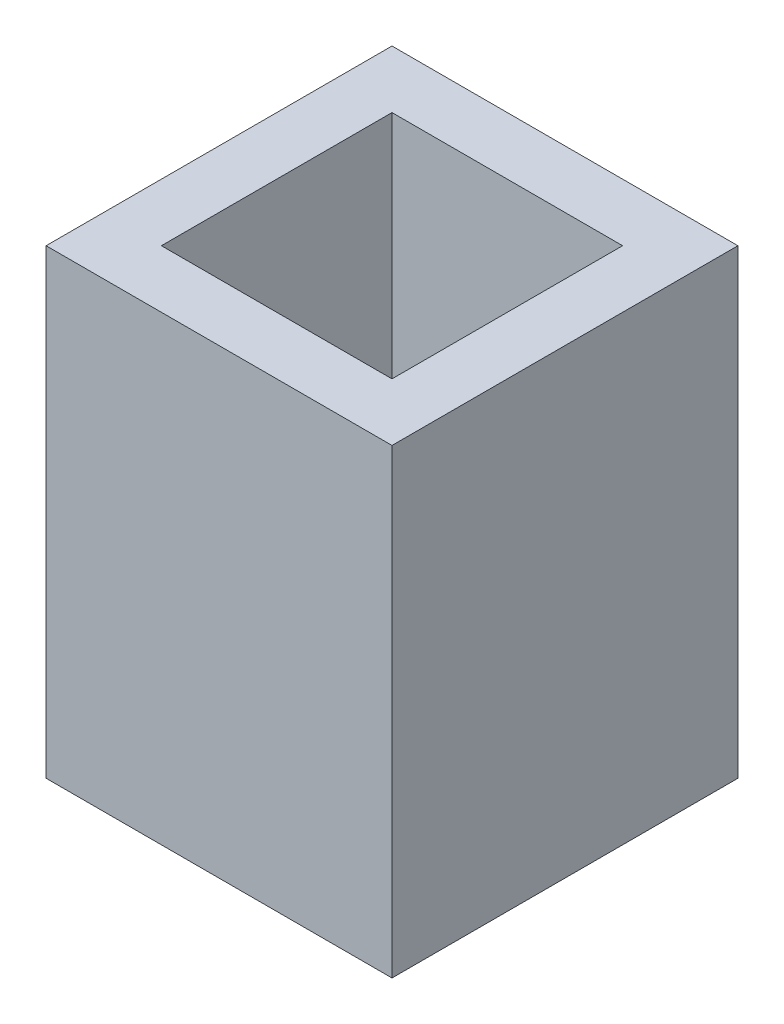
SolidWorks part; units mm, degrees
ref_plane "Front Plane" through (0, 0, 0) normal (0, 0, 1) x (1, 0, 0)
ref_plane "Top Plane" through (0, 0, 0) normal (0, 1, 0) x (1, 0, 0)
ref_plane "Right Plane" through (0, 0, 0) normal (1, 0, 0) x (0, 0, -1)
sketch "Sketch1" plane through (0, 0, 0) normal (0, 1, 0) x (1, 0, 0)
  line L1 (0, 0) -> (19.05, 0)
  line L2 (0, 0) -> (0, 19.05)
  line L3 (0, 19.05) -> (19.05, 19.05)
  line L4 (19.05, 0) -> (19.05, 19.05)
  dimension "D1" = 19.05
  dimension "D2" = 19.05
extrude "Boss-Extrude1" add sketch "Sketch1" along normal blind 25.4
sketch "Sketch2" plane through (0, 25.4, 0) normal (0, 1, 0) x (1, 0, 0)
  line L0 (19.05, 0) -> (19.05, 19.05) construction
  line L1 (3.175, 15.875) -> (15.875, 15.875)
  line L2 (3.175, 15.875) -> (3.175, 3.175)
  line L3 (3.175, 3.175) -> (15.875, 3.175)
  line L4 (15.875, 15.875) -> (15.875, 3.175)
  line L5 (19.05, 19.05) -> (0, 19.05) construction
  dimension "D1" = 12.7
  dimension "D2" = 12.7
  dimension "D3" = 3.175
  dimension "D4" = 3.175
extrude "Cut-Extrude1" cut sketch "Sketch2" against normal blind 406.4
